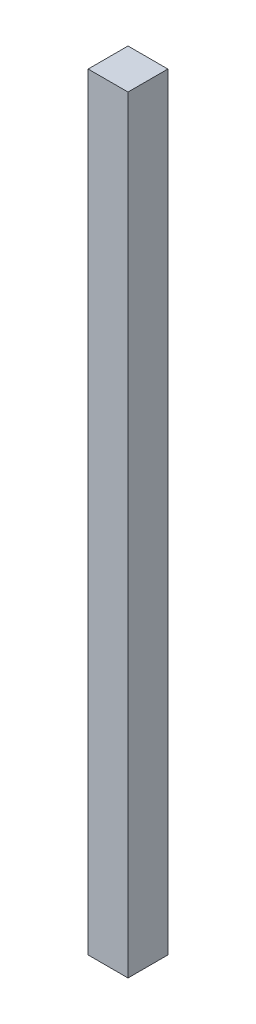
SolidWorks part; units mm, degrees
ref_plane "Plano frontal" through (0, 0, 0) normal (0, 0, 1) x (1, 0, 0)
ref_plane "Plano superior" through (0, 0, 0) normal (0, 1, 0) x (1, 0, 0)
ref_plane "Plano direito" through (0, 0, 0) normal (1, 0, 0) x (0, 0, -1)
sketch "Esboço1" plane through (0, 0, 0) normal (0, 1, 0) x (1, 0, 0)
  line L1 (-0.3, -0.3) -> (0.3, -0.3)
  line L2 (-0.3, -0.3) -> (-0.3, 0.3)
  line L3 (-0.3, 0.3) -> (0.3, 0.3)
  line L4 (0.3, -0.3) -> (0.3, 0.3)
  line L5 (-0.3, -0.3) -> (0.3, 0.3) construction
  line L6 (-0.3, 0.3) -> (0.3, -0.3) construction
  point P0 (0, 0)
  dimension "D1" = 0.6
  dimension "D2" = 0.6
extrude "Ressalto-extrusão1" add sketch "Esboço1" along normal blind 11.55
sketch "Esboço3" plane through (0, 0, 0) normal (0, -1, 0) x (1, 0, 0)
  circle A0 centre (0, 0) radius 0.3
